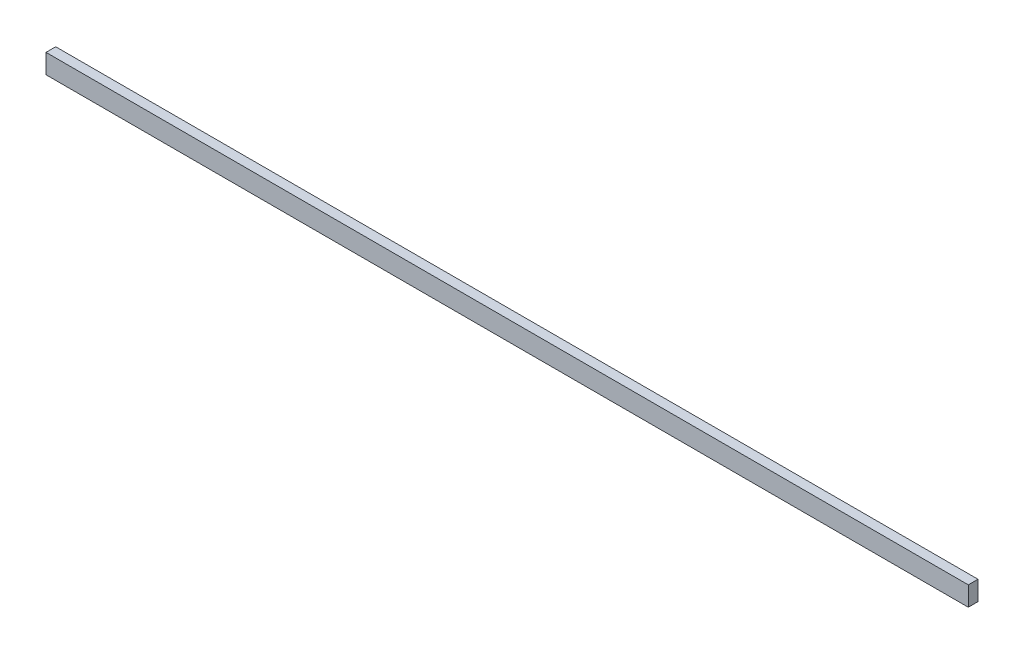
SolidWorks part; units mm, degrees
ref_plane "Front Plane" through (0, 0, 0) normal (0, 0, 1) x (1, 0, 0)
ref_plane "Top Plane" through (0, 0, 0) normal (0, 1, 0) x (1, 0, 0)
ref_plane "Right Plane" through (0, 0, 0) normal (1, 0, 0) x (0, 0, -1)
sketch "Sketch1" plane through (0, 0, 0) normal (0, 0, 1) x (1, 0, 0)
  line L1 (-95, 2) -> (95, 2)
  line L2 (-95, 2) -> (-95, -2)
  line L3 (-95, -2) -> (95, -2)
  line L4 (95, 2) -> (95, -2)
  line L5 (-95, 2) -> (95, -2) construction
  line L6 (-95, -2) -> (95, 2) construction
  point P0 (0, 0)
  dimension "D1" = 4
  dimension "D2" = 190
extrude "Boss-Extrude1" add sketch "Sketch1" along normal blind 2
